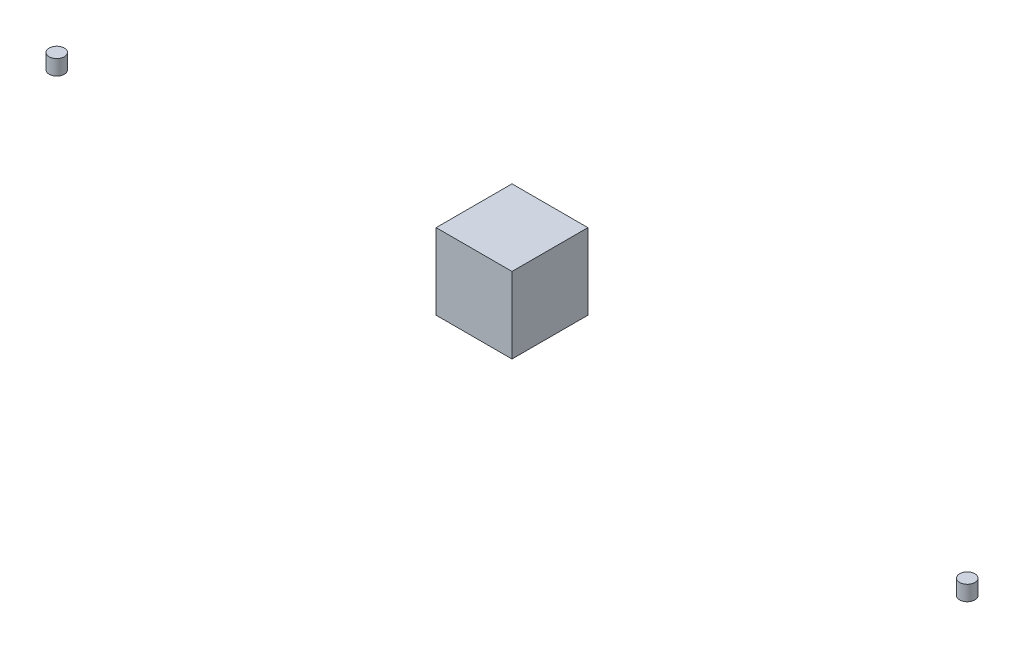
SolidWorks part; units mm, degrees
ref_plane "Front Plane" through (0, 0, 0) normal (0, 0, 1) x (1, 0, 0)
ref_plane "Top Plane" through (0, 0, 0) normal (0, 1, 0) x (1, 0, 0)
ref_plane "Right Plane" through (0, 0, 0) normal (1, 0, 0) x (0, 0, -1)
sketch "Sketch1" plane through (0, 0, 0) normal (0, 1, 0) x (1, 0, 0)
  line L1 (25, -25) -> (-25, -25)
  line L2 (25, -25) -> (25, 25)
  line L3 (25, 25) -> (-25, 25)
  line L4 (-25, -25) -> (-25, 25)
  line L5 (25, -25) -> (-25, 25) construction
  line L6 (25, 25) -> (-25, -25) construction
  point P0 (0, 0)
  dimension "D1" = 50
  dimension "D2" = 50
extrude "Boss-Extrude1" add sketch "Sketch1" along normal blind 50
sketch "Sketch2" plane through (0, 0, 0) normal (0, -1, 0) x (1, 0, 0)
  line L0 (-185.2352, 0) -> (197.3365, 0) construction
  line L1 (0, 0) -> (0, 43.0776) construction
  circle A0 centre (-300, 0) radius 5
  circle A1 centre (300, 0) radius 5
  dimension "D1" = 10
  dimension "D2" = 300
extrude "Boss-Extrude2" add sketch "Sketch2" along normal blind 10 separate body
sketch "Sketch3" plane through (-25, 0, 0) normal (-1, 0, 0) x (0, 0, 1)
  line L0 (-25, 50) -> (25, 50) construction
  line L2 (-25, 50) -> (-25, 0) construction
  circle A0 centre (0, 25) radius 5
  point P4 (0, 0)
  point P6 (-25, 24.024)
  dimension "D1" = 10
  dimension "D2" = 25
  dimension "D3" = 25
extrude "Boss-Extrude3" add sketch "Sketch3" along normal blind 10
